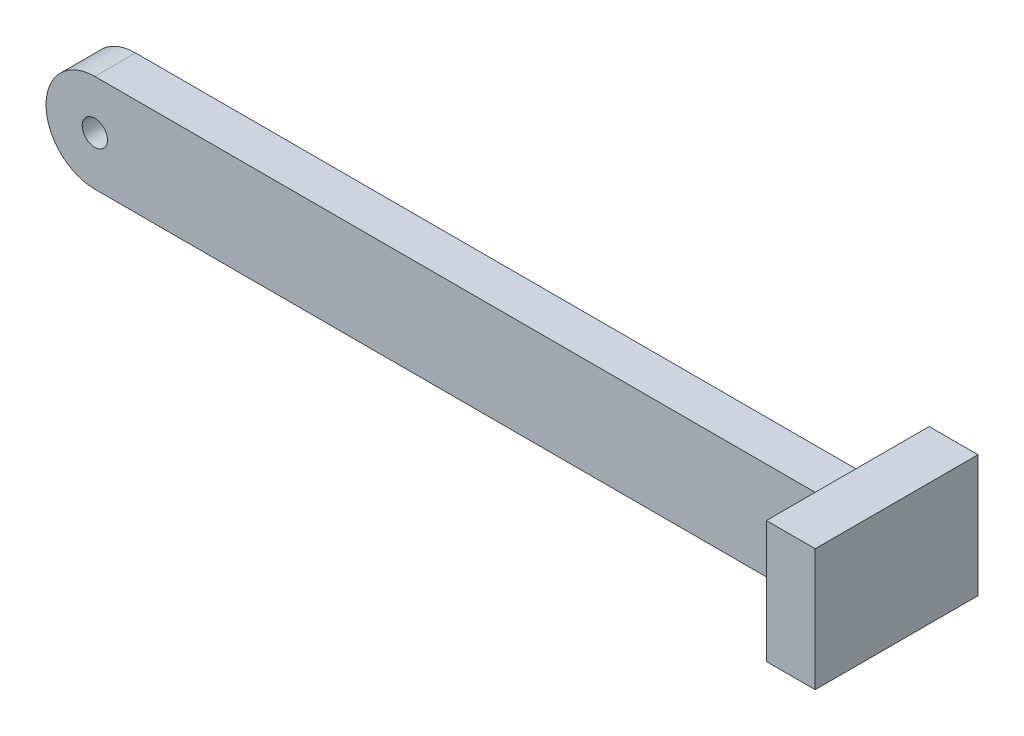
SolidWorks part; units mm, degrees
ref_plane "Front Plane" through (0, 0, 0) normal (0, 0, 1) x (1, 0, 0)
ref_plane "Top Plane" through (0, 0, 0) normal (0, 1, 0) x (1, 0, 0)
ref_plane "Right Plane" through (0, 0, 0) normal (1, 0, 0) x (0, 0, -1)
sketch "Sketch1" plane through (0, 0, 0) normal (0, 0, 1) x (1, 0, 0)
  line L0 (0, 0) -> (90, 0) construction
  line L1 (0, 6) -> (90, 6)
  line L2 (0, -6) -> (90, -6)
  circle A0 centre (0, 0) radius 1.55
  circle A1 centre (90, 0) radius 1.5
  circle A2 centre (0, 0) radius 6
  circle A3 centre (90, 0) radius 6
  dimension "D2" = 3.1
  dimension "D3" = 3
  dimension "D4" = 12
  dimension "D5" = 12
  dimension "D1" = 90
extrude "Boss-Extrude1" add sketch "Sketch1" along normal blind 5
fillet "Fillet3" radius 1 1 edges at (91.5, 0, 0)
sketch "Sketch2" plane through (0, 0, 5) normal (0, 0, 1) x (1, 0, 0)
  circle A0 centre (90, 0) radius 3
sketch "Sketch4" plane through (0, 0, 5) normal (0, 0, 1) x (1, 0, 0)
  line L1 (90, -7.5) -> (96, -7.5)
  line L2 (90, -7.5) -> (90, 7.5)
  line L3 (90, 7.5) -> (96, 7.5)
  line L4 (96, -7.5) -> (96, 7.5)
  dimension "D1" = 6
  dimension "D2" = 15
  dimension "D3" = 7.5
extrude "Boss-Extrude2" add sketch "Sketch4" against normal blind 20 from offset 7.5
